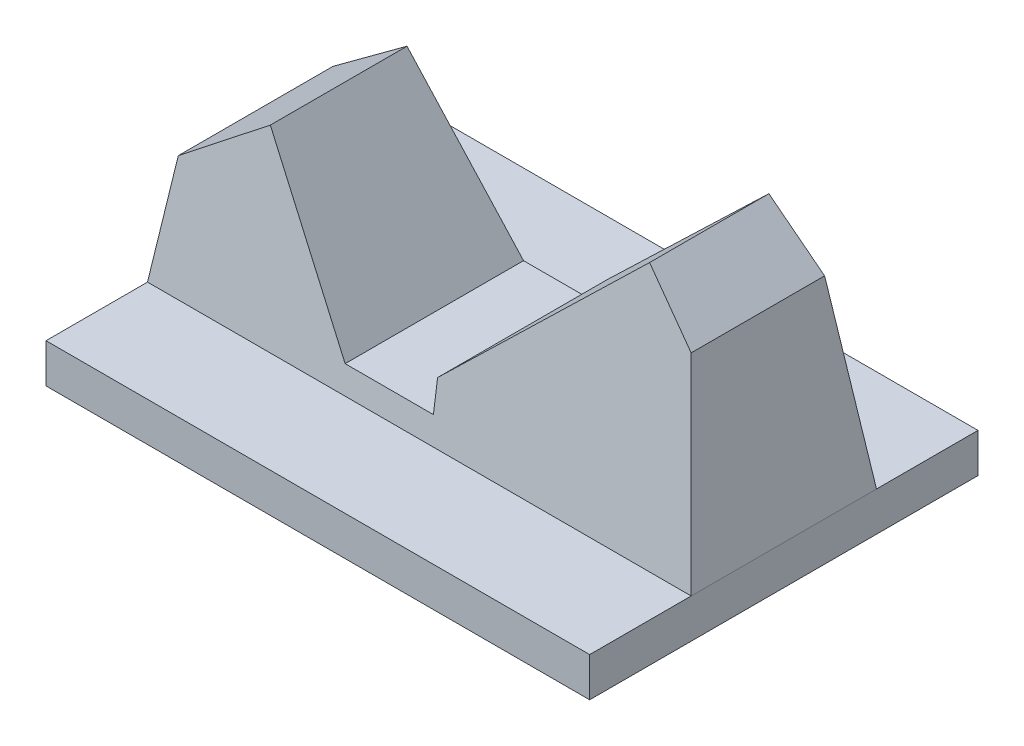
SolidWorks part; units mm, degrees
ref_plane "Front Plane" through (0, 0, 0) normal (0, 0, 1) x (1, 0, 0)
ref_plane "Top Plane" through (0, 0, 0) normal (0, 1, 0) x (1, 0, 0)
ref_plane "Right Plane" through (0, 0, 0) normal (1, 0, 0) x (0, 0, -1)
sketch "Sketch1" plane through (0, 0, 0) normal (0, 1, 0) x (1, 0, 0)
  line L0 (0, -27.94) -> (0, 27.94) construction
  line L1 (-39.116, 27.94) -> (39.116, 27.94)
  line L2 (-39.116, 27.94) -> (-39.116, -27.94)
  line L3 (-39.116, -27.94) -> (39.116, -27.94)
  line L4 (39.116, 27.94) -> (39.116, -27.94)
  line L5 (39.116, 0) -> (-39.116, 0) construction
  dimension "D1" = 78.232
  dimension "D2" = 55.88
extrude "Boss-Extrude1" add sketch "Sketch1" along normal blind 5.6388 contours L1 L4 L3 L2
sketch "Sketch2" plane through (0, 5.6388, 0) normal (0, 1, 0) x (1, 0, 0)
  line L0 (-39.116, 27.94) -> (-39.116, -27.94) construction
  line L1 (-39.116, 13.335) -> (39.116, 13.335)
  line L2 (-39.116, 13.335) -> (-39.116, -13.335)
  line L3 (-39.116, -13.335) -> (39.116, -13.335)
  line L4 (39.116, 13.335) -> (39.116, -13.335)
  line L5 (39.116, 27.94) -> (39.116, -27.94) construction
  line L6 (-39.116, 0) -> (39.116, 0) construction
  point P10 (0, 0)
  dimension "D1" = 26.67
extrude "Boss-Extrude2" add sketch "Sketch2" along normal blind 38.1 draft 8
sketch3d "3DSketch1"
  line L0 (39.116, 28.3353, 0) -> (28.3827, 39.45, 0)
  line L1 (28.3827, 39.45, 0) -> (1.524, 13.5128, 0)
  line L2 (1.524, 13.5128, 0) -> (1.524, 9.1948, 0)
  line L3 (1.524, 9.1948, 0) -> (-11.176, 9.1948, 0)
  line L4 (-11.176, 9.1948, 0) -> (-24.9418, 30.5411, 0)
  line L5 (-24.9418, 30.5411, 0) -> (-39.116, 19.704, 0)
  line L6 (-39.116, 19.704, 0) -> (-39.116, 43.7388, 0)
  line L7 (-39.116, 43.7388, 0) -> (39.116, 43.7388, 0)
  line L8 (39.116, 43.7388, 0) -> (39.116, 28.3353, 0)
  point P9 (0, 0, 0)
  point P10 (0, 0, 0)
  point P11 (-11.9229, 6.9159, 0)
  dimension "D1" = 44
  dimension "D2" = 37.338
  dimension "D3" = 12.7
  dimension "D4" = 25.4
  dimension "D5" = 4.318
  dimension "D6" = 40.64
  dimension "D7" = 7.874
extrude "Cut-Extrude1" cut sketch "3DSketch1" along direction (0, 0, -1) on the side against the normal mid plane 38.1
